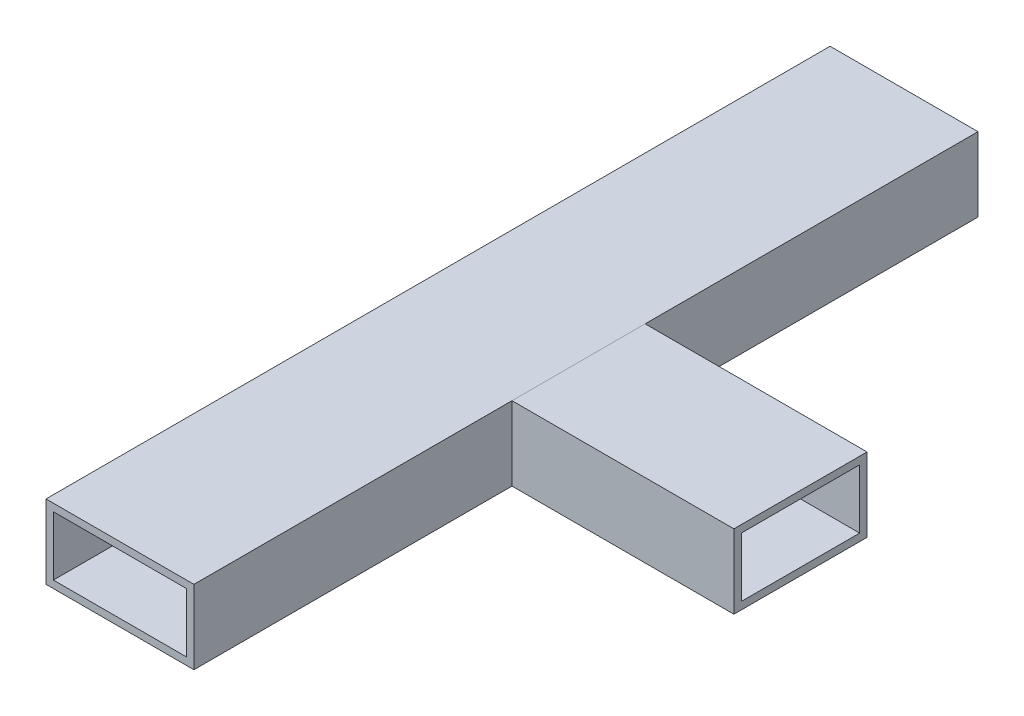
SolidWorks part; units mm, degrees
ref_plane "前视基准面" through (0, 0, 0) normal (0, 0, 1) x (1, 0, 0)
ref_plane "上视基准面" through (0, 0, 0) normal (0, 1, 0) x (1, 0, 0)
ref_plane "右视基准面" through (0, 0, 0) normal (1, 0, 0) x (0, 0, -1)
sketch "草图1" plane through (0, 0, 0) normal (0, 0, 1) x (1, 0, 0)
  line L1 (9, -4) -> (-9, -4)
  line L2 (9, -4) -> (9, 4)
  line L3 (9, 4) -> (-9, 4)
  line L4 (-9, -4) -> (-9, 4)
  line L5 (9, -4) -> (-9, 4) construction
  line L6 (9, 4) -> (-9, -4) construction
  line L7 (10, -5) -> (-10, -5)
  line L8 (10, -5) -> (10, 5)
  line L9 (10, 5) -> (-10, 5)
  line L10 (-10, -5) -> (-10, 5)
  line L11 (10, -5) -> (-10, 5) construction
  line L12 (10, 5) -> (-10, -5) construction
  point P0 (0, 0)
  point P6 (0, 0)
  dimension "D1" = 8
  dimension "D2" = 10
  dimension "D3" = 18
  dimension "D4" = 20
extrude "凸台-拉伸1" add sketch "草图1" along normal blind 106
sketch "草图2" plane through (10, 0, 0) normal (1, 0, 0) x (0, 0, -1)
  line L0 (-63, 5) -> (-63, -5)
  line L1 (-106, 5) -> (0, 5) construction
  line L2 (-106, -5) -> (0, -5) construction
  line L3 (-63, -5) -> (-45, -5)
  line L4 (-45, -5) -> (-45, 5)
  line L5 (-45, 5) -> (-63, 5)
  line L6 (-46, 4) -> (-62, 4)
  line L7 (-62, 4) -> (-62, -4)
  line L8 (-62, -4) -> (-46, -4)
  line L9 (-46, -4) -> (-46, 4)
  line L10 (-106, -5) -> (-106, 5) construction
  point P6 (-54, 5)
  dimension "D1" = 9
  dimension "D2" = 1
  dimension "D3" = 43
extrude "凸台-拉伸2" add sketch "草图2" along normal blind 30 separate body
